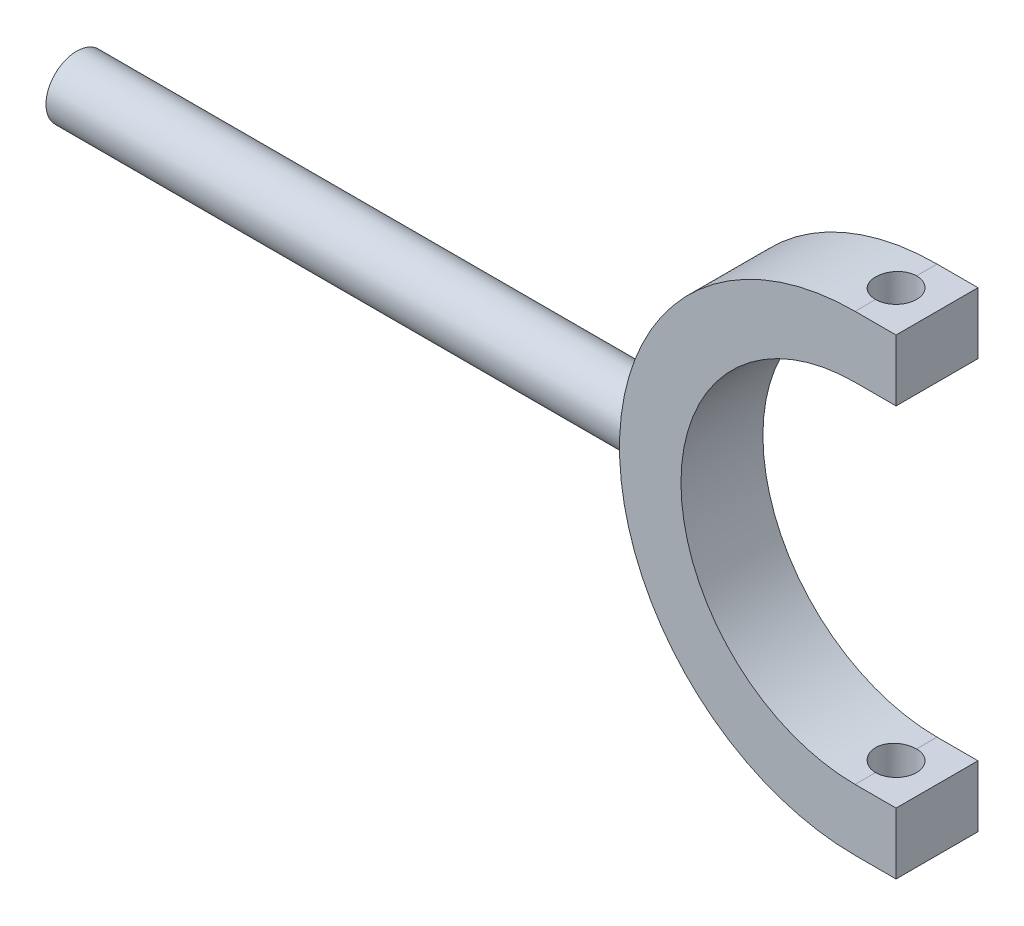
SolidWorks part; units mm, degrees
ref_plane "Alzado" through (0, 0, 0) normal (0, 0, 1) x (1, 0, 0)
ref_plane "Planta" through (0, 0, 0) normal (0, 1, 0) x (1, 0, 0)
ref_plane "Vista lateral" through (0, 0, 0) normal (1, 0, 0) x (0, 0, -1)
sketch "Croquis2" plane through (0, 0, 0) normal (1, 0, 0) x (0, 0, -1)
  circle A0 centre (0, 0) radius 7.5
  dimension "D1" = 15
extrude "Saliente-Extruir1" add sketch "Croquis2" against normal blind 200
sketch "Croquis3" plane through (0, 0, 0) normal (1, 0, 0) x (0, 0, -1)
  line L0 (0, -50) -> (0, 50) construction
  line L2 (-10, 57.5) -> (10, 57.5)
  line L3 (-10, 57.5) -> (-10, 42.5)
  line L4 (-10, 42.5) -> (10, 42.5)
  line L5 (10, 57.5) -> (10, 42.5)
  line L6 (-10, 57.5) -> (10, 42.5) construction
  line L7 (-10, 42.5) -> (10, 57.5) construction
  dimension "D1" = 100
  dimension "D2" = 50
  dimension "D3" = 20
  dimension "D4" = 15
sketch "Croquis4" plane through (0, 0, 0) normal (0, 0, 1) x (1, 0, 0)
  arc A0 (0, 50) -> (0, -50) centre (0, 0) ccw
sweep "Barrer1" add profiles "Croquis3" path "Croquis4"
sketch "Croquis5" plane through (0, 0, 10) normal (0, 0, 1) x (1, 0, 0)
  circle A0 centre (0, 0) radius 42.5
extrude "Cortar-Extruir1" cut sketch "Croquis5" against normal blind 100
sketch "Croquis6" plane through (0, 0, 0) normal (1, 0, 0) x (0, 0, -1)
  line L4 (10, 42.5) -> (10, 57.5)
  line L5 (10, 57.5) -> (-10, 57.5)
  line L6 (-10, 57.5) -> (-10, 42.5)
  line L7 (-10, 42.5) -> (10, 42.5)
  line L8 (10, 42.5) -> (10, 57.5)
  line L9 (10, 57.5) -> (-10, 57.5)
  line L10 (-10, 57.5) -> (-10, 42.5)
  line L11 (-10, 42.5) -> (10, 42.5)
  dimension "D1" = 0
extrude "Saliente-Extruir2" add sketch "Croquis6" along normal blind 10
mirror "Simetría1" about plane through (0, 0, 0) normal (0, 1, 0) of "Saliente-Extruir2"
sketch "Croquis8" plane through (0, 57.5, 0) normal (0, 1, 0) x (1, 0, 0)
  circle A0 centre (0, 0) radius 5
  dimension "D1" = 10
extrude "Cortar-Extruir2" cut sketch "Croquis8" against normal through all
